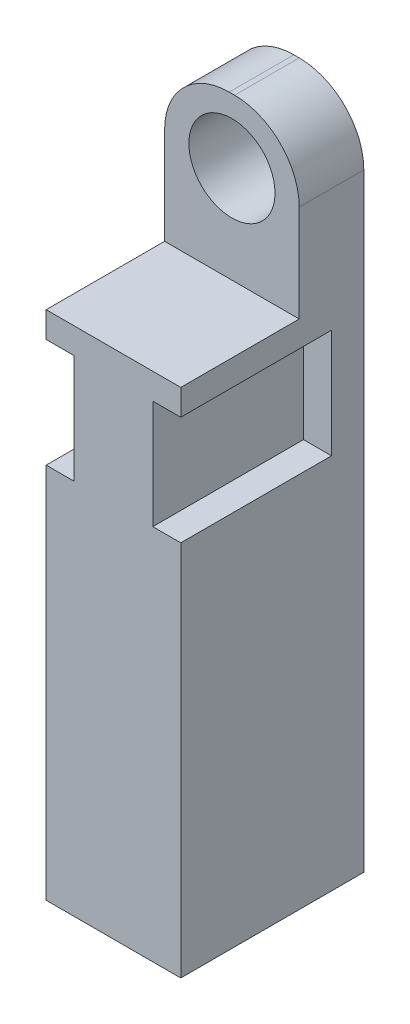
SolidWorks part; units mm, degrees
ref_plane "Front Plane" through (0, 0, 0) normal (0, 0, 1) x (1, 0, 0)
ref_plane "Top Plane" through (0, 0, 0) normal (0, 1, 0) x (1, 0, 0)
ref_plane "Right Plane" through (0, 0, 0) normal (1, 0, 0) x (0, 0, -1)
sketch "Sketch1" plane through (0, 0, 0) normal (0, 1, 0) x (1, 0, 0)
  line L7 (-10.25, 10.25) -> (10.25, 10.25)
  line L8 (-10.25, 10.25) -> (-10.25, -10.25)
  line L9 (-10.25, -10.25) -> (10.25, -10.25)
  line L10 (10.25, 10.25) -> (10.25, -10.25)
  line L11 (-10.25, 10.25) -> (10.25, -10.25) construction
  line L12 (-10.25, -10.25) -> (10.25, 10.25) construction
  line L13 (-12.5, -12.5) -> (12.5, -12.5)
  line L14 (-12.5, -12.5) -> (-12.5, 21.5)
  line L15 (-12.5, 21.5) -> (12.5, 21.5)
  line L16 (12.5, -12.5) -> (12.5, 21.5)
  point P0 (0, 0)
  point P6 (0, 0)
extrude "Boss-Extrude1" add sketch "Sketch1" along normal blind 40
sketch "Sketch2" plane through (0, 40, 0) normal (0, 1, 0) x (1, 0, 0)
  line L1 (-12.5, 21.5) -> (12.5, 21.5)
  line L2 (-12.5, 21.5) -> (-12.5, -12.5)
  line L3 (-12.5, -12.5) -> (12.5, -12.5)
  line L4 (12.5, 21.5) -> (12.5, -12.5)
extrude "Boss-Extrude2" add sketch "Sketch2" along normal blind 55
sketch "Sketch3" plane through (0, 95, 0) normal (0, 1, 0) x (1, 0, 0)
  line L1 (-12.5, 21.5) -> (12.5, 21.5)
  line L2 (-12.5, 21.5) -> (-12.5, 9.5)
  line L3 (-12.5, 9.5) -> (12.5, 9.5)
  line L4 (12.5, 21.5) -> (12.5, 9.5)
extrude "Boss-Extrude3" add sketch "Sketch3" along normal blind 20
sketch "Sketch4" plane through (0, 115, 0) normal (0, 1, 0) x (1, 0, 0)
  line L0 (12.5, -12.5) -> (12.5, 9.5) construction
  line L1 (-12.5, 21.5) -> (12.5, 21.5)
  line L2 (-12.5, 21.5) -> (-12.5, 9.5)
  line L3 (-12.5, 9.5) -> (12.5, 9.5)
  line L4 (12.5, 21.5) -> (12.5, 9.5)
  line L5 (-12.5, 9.5) -> (12.5, 9.5) construction
extrude "Boss-Extrude4" add sketch "Sketch4" along normal blind 10
sketch "Sketch6" plane through (0, 0, -9.5) normal (0, 0, 1) x (1, 0, 0)
  line L0 (12.5, 95) -> (12.5, 113)
  line L1 (12.5, 125) -> (12.5, 95) construction
  circle A3 centre (0, 113) radius 8
extrude "Cut-Extrude1" cut sketch "Sketch6" against normal blind 12 contours A3
fillet "Fillet1" radius 12 2 edges at (12.5, 125, -15.5) (-12.5, 125, -15.5)
sketch "Sketch7" plane through (0, 0, 12.5) normal (0, 0, 1) x (1, 0, 0)
  line L0 (12.5, 95) -> (12.5, 90.2)
  line L2 (-12.5, 95) -> (-12.5, 90.2)
  line L5 (-12.5, 90.2) -> (-7.3, 90.2)
  line L6 (-12.5, 90.2) -> (-12.5, 70)
  line L7 (-12.5, 70) -> (-7.3, 70)
  line L8 (-7.3, 90.2) -> (-7.3, 70)
  line L9 (12.5, 95) -> (12.5, 0) construction
  line L11 (12.5, 90.2) -> (7.3, 90.2)
  line L12 (12.5, 90.2) -> (12.5, 70)
  line L13 (12.5, 70) -> (7.3, 70)
  line L14 (7.3, 90.2) -> (7.3, 70)
  dimension "D1" = 4.8
  dimension "D2" = 4.8
extrude "Cut-Extrude2" cut sketch "Sketch7" against normal blind 28 contours L6 L7 L8 L5 | L12 L13 L14 L11
